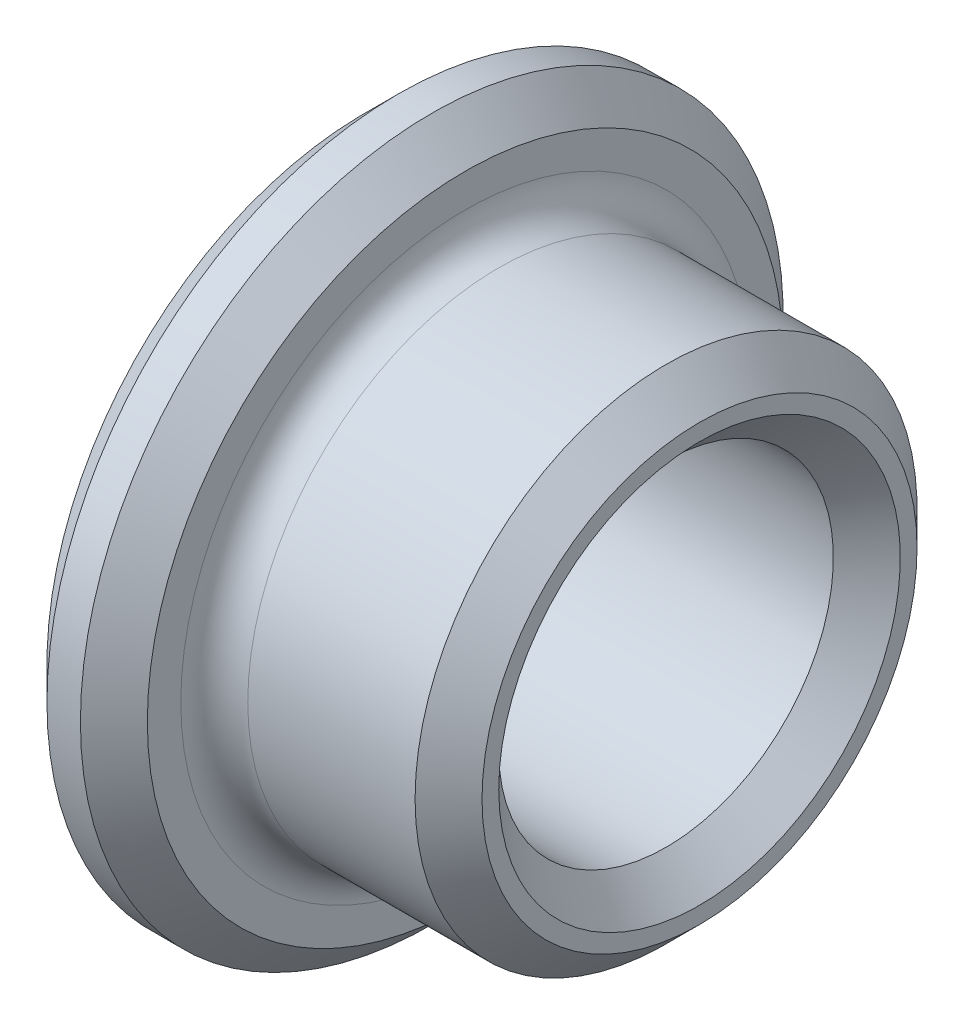
SolidWorks part; units mm, degrees
material "Phosphor bronze 10% D, UNS C52400"
ref_plane "Front Plane" through (0, 0, 0) normal (0, 0, 1) x (1, 0, 0)
ref_plane "Top Plane" through (0, 0, 0) normal (0, 1, 0) x (1, 0, 0)
ref_plane "Right Plane" through (0, 0, 0) normal (1, 0, 0) x (0, 0, -1)
sketch "Sketch1" plane through (0, 0, 0) normal (0, 0, 1) x (1, 0, 0)
  line L0 (0, 5) -> (10, 5)
  line L1 (10, 5) -> (10, 7.5)
  line L2 (10, 7.5) -> (3, 7.5)
  line L3 (3, 7.5) -> (3, 10.5)
  line L4 (3, 10.5) -> (0, 10.5)
  line L5 (0, 10.5) -> (0, 5)
  line L6 (0, 0) -> (44.8454, 0) construction
  dimension "D1" = 10
  dimension "D2" = 3
  dimension "D3" = 21
  dimension "D4" = 10
  dimension "D5" = 15
revolve "Revolve1" add sketch "Sketch1" angle 360 about L6
chamfer "Chamfer1" distance 1 angle 45 5 edges at (0, 0, 5) (10, 0, 5) (3, 0, 10.5) (0, 0, 10.5) (10, 0, 7.5)
fillet "Fillet1" radius 1 1 edges at (3, 0, 7.5)
move or copy body "Body-Move/Copy1" [suppressed] bodies to move or copy 101
